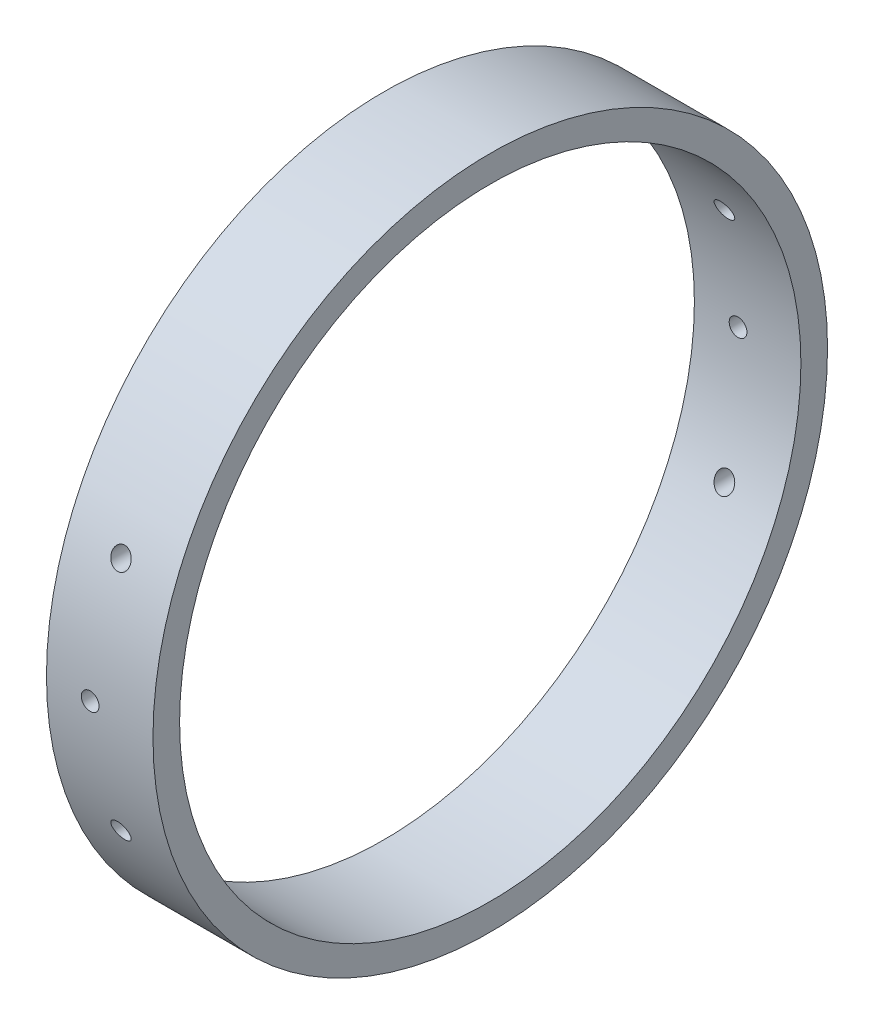
SolidWorks part; units mm, degrees
material "Refractory cement"
ref_plane "Front Plane" through (0, 0, 0) normal (0, 0, 1) x (1, 0, 0)
ref_plane "Top Plane" through (0, 0, 0) normal (0, 1, 0) x (1, 0, 0)
ref_plane "Right Plane" through (0, 0, 0) normal (1, 0, 0) x (0, 0, -1)
sketch "Sketch1" plane through (0, 0, 0) normal (1, 0, 0) x (0, 0, -1)
  circle A0 centre (0, 0) radius 875
  circle A1 centre (0, 0) radius 950
  dimension "D1" = 1900
  dimension "D2" = 1750
extrude "Boss-Extrude1" add sketch "Sketch1" along normal mid plane 300
sketch "Sketch2" plane through (0, 0, 1158) normal (0, 0, 1) x (1, 0, 0)
  circle A0 centre (-27, 0) radius 25
  circle A1 centre (0, 332) radius 27
  circle A2 centre (0, -332) radius 27
  dimension "D2" = 50
  dimension "D3" = 54
  dimension "D4" = 54
  dimension "D1" = 27
extrude "Cut-Extrude1" cut sketch "Sketch2" against normal through all
